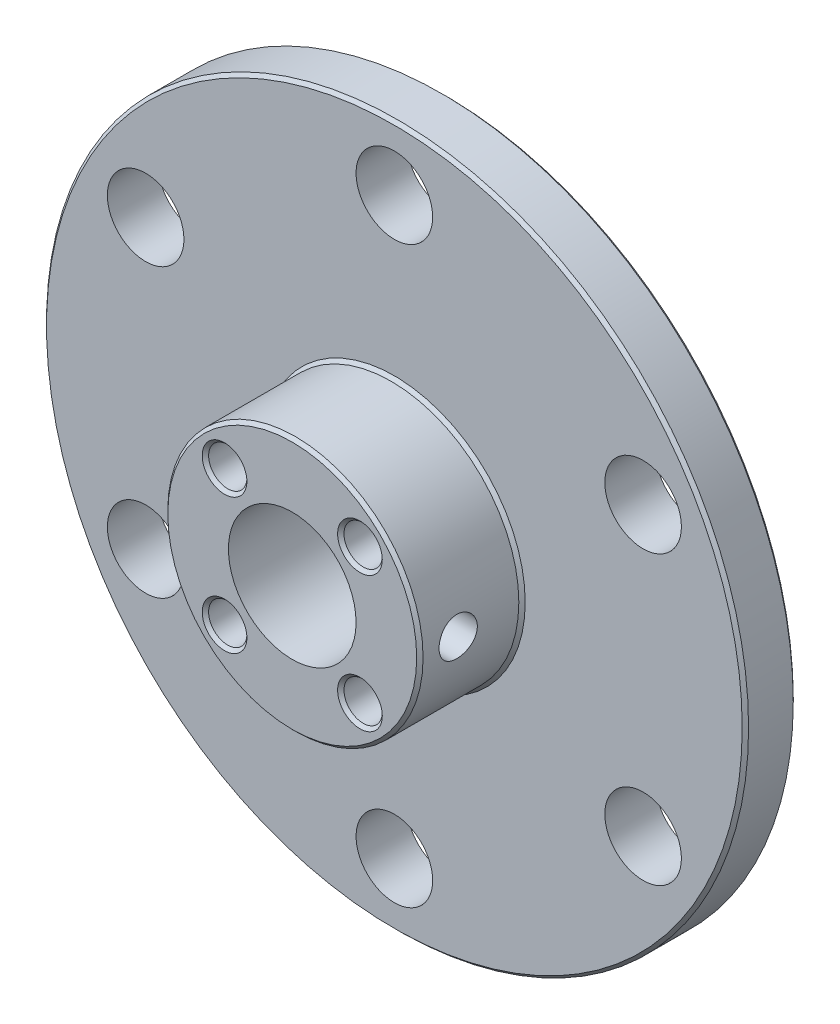
SolidWorks part; units mm, degrees
ref_plane "Front Plane" through (0, 0, 0) normal (0, 0, 1) x (1, 0, 0)
ref_plane "Top Plane" through (0, 0, 0) normal (0, 1, 0) x (1, 0, 0)
ref_plane "Right Plane" through (0, 0, 0) normal (1, 0, 0) x (0, 0, -1)
sketch "Sketch1" plane through (0, 0, 0) normal (0, 0, 1) x (1, 0, 0)
  circle A0 centre (0, 0) radius 27.5
  circle A1 centre (0, 0) radius 22.5 construction
  circle A2 centre (0, 22.5) radius 3
  circle A3 centre (19.4856, 11.25) radius 3
  circle A4 centre (19.4856, -11.25) radius 3
  circle A5 centre (0, -22.5) radius 3
  circle A6 centre (-19.4856, -11.25) radius 3
  circle A7 centre (-19.4856, 11.25) radius 3
  point P18 (0, 0)
  dimension "D1" = 55
  dimension "D2" = 45
  dimension "D3" = 6
  dimension "D4" = 6
extrude "Boss-Extrude1" add sketch "Sketch1" along normal blind 4
sketch "Sketch2" plane through (0, 0, 4) normal (0, 0, 1) x (1, 0, 0)
  circle A0 centre (0, 0) radius 10
  dimension "D1" = 20
extrude "Boss-Extrude2" add sketch "Sketch2" along normal blind 8
sketch "Sketch3" plane through (0, 0, 0) normal (0, 0, -1) x (-1, 0, 0)
  circle A0 centre (0, 0) radius 15
  dimension "D1" = 30
  dimension "D2" = 30
extrude "Boss-Extrude3" add sketch "Sketch3" along normal blind 1.5
sketch "Sketch4" plane through (0, 0, 12) normal (0, 0, 1) x (1, 0, 0)
  line L0 (0, 0) -> (-5.3033, 5.3033) construction
  line L1 (0, 0) -> (0, 7.5) construction
  circle A0 centre (0, 0) radius 7.5 construction
  circle A1 centre (-5.3033, 5.3033) radius 1.5
  circle A2 centre (5.3033, 5.3033) radius 1.5
  circle A3 centre (5.3033, -5.3033) radius 1.5
  circle A4 centre (-5.3033, -5.3033) radius 1.5
  point P15 (0, 0)
  dimension "D1" = 15
  dimension "D2" = 3
  dimension "D3" = 45
  dimension "D4" = 4
extrude "Cut-Extrude2" cut sketch "Sketch4" against normal blind 6
sketch "Sketch5" plane through (0, 0, 0) normal (1, 0, 0) x (0, 0, -1)
  line L0 (-4, 27.5) -> (-4, -27.5) construction
  circle A0 centre (-9, 0) radius 1.5
  dimension "D1" = 3
  dimension "D2" = 5
extrude "Cut-Extrude3" cut sketch "Sketch5" against normal blind 3.5 from offset 10
mirror "Mirror1" about plane through (0, 0, 0) normal (1, 0, 0) of "Cut-Extrude3"
sketch "Sketch6" plane through (0, 0, 12) normal (0, 0, 1) x (1, 0, 0)
  circle A0 centre (0, 0) radius 5
  dimension "D1" = 10
extrude "Cut-Extrude4" cut sketch "Sketch6" against normal blind 10
sketch "Sketch7" plane through (0, 0, -1.5) normal (0, 0, -1) x (-1, 0, 0)
  circle A0 centre (0, 0) radius 4
  dimension "D1" = 8
extrude "Cut-Extrude5" cut sketch "Sketch7" against normal through all
chamfer "Chamfer1" distance 0.25 angle 45 4 edges at (6.8033, 5.3033, 12) (-3.8033, 5.3033, 12) (-3.8033, -5.3033, 12) (6.8033, -5.3033, 12)
chamfer "Chamfer2" distance 0.25 angle 45 6 edges at (-15, 0, -1.5) (15, 0, 0) (27.5, 0, 0) (10, 0, 4) (10, 0, 12) (27.5, 0, 4)
